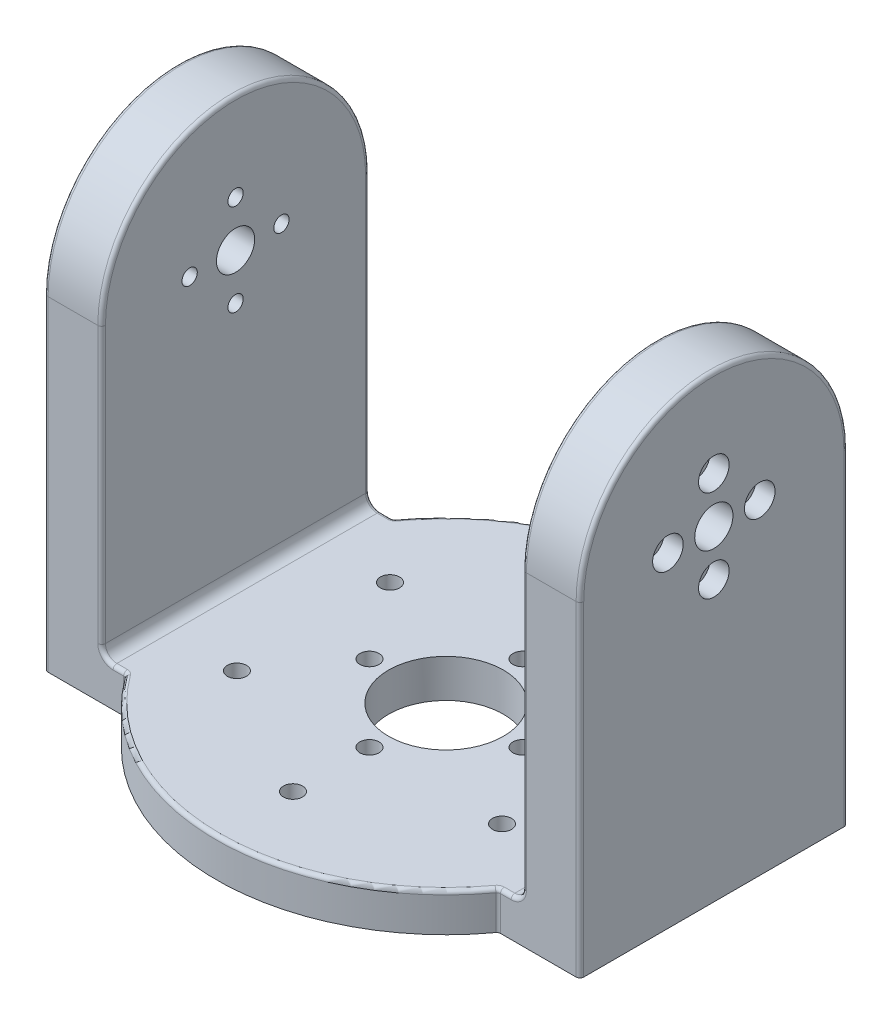
SolidWorks part; units mm, degrees
material "ESUN PLA +"
ref_plane "Front Plane" through (0, 0, 0) normal (0, 0, 1) x (1, 0, 0)
ref_plane "Top Plane" through (0, 0, 0) normal (0, 1, 0) x (1, 0, 0)
ref_plane "Right Plane" through (0, 0, 0) normal (1, 0, 0) x (0, 0, -1)
sketch "Sketch1" plane through (0, 0, 0) normal (1, 0, 0) x (0, 0, -1)
  line L0 (-35, 0) -> (35, 0)
  line L3 (-35, 0) -> (-35, 85)
  line L4 (-35, 85) -> (35, 85) construction
  line L5 (0, 120) -> (0, 0) construction
  line L9 (35, 85) -> (35, 0)
  arc A0 (0, 120) -> (-35, 85) centre (0, 85) ccw
  circle A1 centre (0, 85) radius 5
  arc A2 (0, 120) -> (35, 85) centre (0, 85) cw
  point P4 (0, 0)
  dimension "D1" = 70
  dimension "D3" = 10
  dimension "D2" = 120
extrude "Boss-Extrude1" add sketch "Sketch1" along normal mid plane 140
sketch "Sketch2" plane through (0, 0, 0) normal (0, 0, 1) x (1, 0, 0)
  line L1 (-55, 120) -> (55, 120)
  line L2 (-55, 120) -> (-55, 10)
  line L3 (-55, 10) -> (55, 10)
  line L4 (55, 120) -> (55, 10)
  line L5 (70, 0) -> (-70, 0) construction
  line L6 (-70, 85) -> (-70, 0) construction
  line L7 (70, 85) -> (70, 120) construction
  line L8 (70, 120) -> (-70, 120) construction
  dimension "D1" = 10
  dimension "D2" = 15
  dimension "D3" = 15
extrude "Cut-Extrude1" cut sketch "Sketch2" against normal through all both and the other way through all
sketch "Sketch10" plane through (0, 0, 0) normal (0, -1, 0) x (1, 0, 0)
  circle A0 centre (0, 0) radius 60
  dimension "D1" = 120
extrude "Boss-Extrude3" add sketch "Sketch10" against normal blind 10
sketch "Sketch6" plane through (0, 10, 0) normal (0, 1, 0) x (1, 0, 0)
  circle A0 centre (0, 0) radius 15
  dimension "D1" = 30
extrude "Cut-Extrude5" cut sketch "Sketch6" against normal through all both and the other way through all
sketch "Sketch7" plane through (70, 0, 0) normal (1, 0, 0) x (0, 0, -1)
  circle A0 centre (0, 85) radius 12 construction
  circle A1 centre (0, 73) radius 2
  point P0 (0, 85)
  dimension "D1" = 4
  dimension "D2" = 24
extrude "Cut-Extrude6" cut sketch "Sketch7" against normal up to next and the other way through all
sketch "Sketch8" plane through (70, 0, 0) normal (-1, 0, 0) x (0, 0, 1)
  circle A0 centre (0, 73) radius 4
  dimension "D1" = 8
extrude "Cut-Extrude7" cut sketch "Sketch8" along normal blind 5
pattern_circular "CirPattern1" count 4 over 360 about axis through (0, 85, 0) along (1, 0, 0) of "Cut-Extrude6", "Cut-Extrude7"
mirror "Mirror2" about plane through (0, 0, 0) normal (1, 0, 0) of "CirPattern1", "Cut-Extrude6", "Cut-Extrude7"
sketch "Sketch11" plane through (0, 10, 0) normal (0, 1, 0) x (1, 0, 0)
  circle A0 centre (0, -40) radius 1.7
  dimension "D1" = 3.4
  dimension "D2" = 40
extrude "Cut-Extrude8" cut sketch "Sketch11" against normal through all both and the other way through all
sketch "Sketch12" plane through (0, 10, 0) normal (0, 1, 0) x (1, 0, 0)
  circle A0 centre (0, -40) radius 2.5
  dimension "D1" = 5
extrude "Cut-Extrude9" cut sketch "Sketch12" against normal blind 5
pattern_circular "CirPattern2" count 6 over 360 about axis through (0, 0, 0) along (0, 1, 0) of "Cut-Extrude8", "Cut-Extrude9"
sketch "Sketch13" plane through (0, 10, 0) normal (0, 1, 0) x (1, 0, 0)
  circle A0 centre (0, -20) radius 1.7
  dimension "D1" = 20
  dimension "D2" = 3.4
extrude "Cut-Extrude10" cut sketch "Sketch13" against normal through all both and the other way through all
sketch "Sketch14" plane through (0, 10, 0) normal (0, 1, 0) x (1, 0, 0)
  circle A0 centre (0, -20) radius 2.5
  dimension "D1" = 5
extrude "Cut-Extrude11" cut sketch "Sketch14" against normal blind 5
pattern_circular "CirPattern3" count 4 over 360 about axis through (0, 0, 0) along (0, 1, 0) of "Cut-Extrude10", "Cut-Extrude11"
fillet "Fillet2" radius 3 2 edges at (-55, 10, 0) (55, 10, 0)
fillet "Fillet1" radius 1 26 edges at (55, 49, -35) (55, 120, 0) (70, 42.5, -35) (70, 120, 0) (-70, 42.5, -35) (-70, 120, 0) (-55, 49, -35) (-55, 120, 0) (48.734, 5, -35) (-48.734, 5, -35) (-48.734, 5, 35) (48.734, 5, 35) (55, 49, 35) (70, 42.5, 35) (-70, 42.5, 35) (-55, 49, 35) (0, 10, -60) (0, 10, 60) (50.367, 10, 35) (54.1213, 10.8787, 35) (50.367, 10, -35) (54.1213, 10.8787, -35) (-50.367, 10, -35) (-54.1213, 10.8787, -35) (-50.367, 10, 35) (-54.1213, 10.8787, 35)
